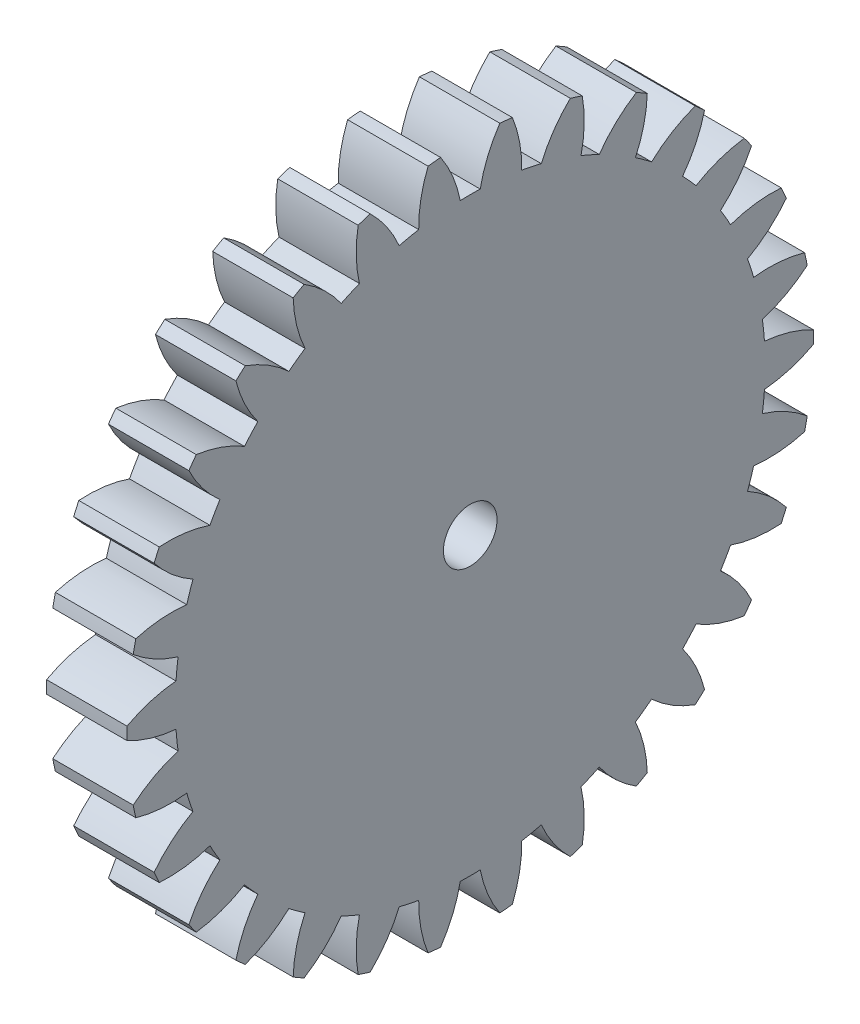
SolidWorks part; units mm, degrees
ref_plane "Plane1" through (0, 0, 0) normal (0, 0, 1) x (1, 0, 0)
ref_plane "Plane2" through (0, 0, 0) normal (0, 1, 0) x (1, 0, 0)
ref_plane "Plane3" through (0, 0, 0) normal (1, 0, 0) x (0, 0, -1)
sketch "HoldingSke" plane through (0, 0, 0) normal (0, 1, 0) x (1, 0, 0)
  line L0 (0, 0) -> (1.0825, -0.625)
  line L1 (-15, 0) -> (100, 0) construction
  line L2 (0, 0) -> (-2.1039, 2.3779)
  line L3 (0, 0) -> (-11.863, 4.5341)
  line L4 (0, 0) -> (7.479, 4.318)
  line L5 (0, 0) -> (-46.8476, -17.4728)
  line L6 (0, 0) -> (-2.4869, -1.6779)
  line L7 (-2.1039, 2.3779) -> (8.6586, 51.2059)
  line L8 (-76.2, 54.61) -> (-75.9, 54.61)
  line L9 (-71.009, 38.7566) -> (-53.1078, 45.2721)
  line L10 (-76.2, 71.12) -> (104.1128, 71.12)
  line L11 (0, 0) -> (-3, 0)
  line L12 (-76.2, 101.6) -> (-76.17, 101.6)
  line L13 (24.9733, 27.94) -> (52.9518, 28.4284)
  line L14 (24.9733, 27.94) -> (24.9743, 27.94)
  line L15 (24.9733, 27.94) -> (100.4006, 29.5858)
  line L16 (-63.627, -0.8) -> (-12.827, -0.8)
  circle A0 centre (0, 0) radius 1
  circle A1 centre (0, 0) radius 10.999
  circle A2 centre (0, 0) radius 37.5
  circle A3 centre (0, 0) radius 1
  dimension "MHD" = 21.998
  dimension "Hub_dia" = 75
  dimension "Bore" = 2
  dimension "MBD" = 2
  dimension "Num_teeth" = 30
  dimension "Pitch" = 1.25
  dimension "Overall_len" = 50
  dimension "Show_teeth" = 30
  dimension "Thickness" = 3
  dimension "OAL" = 50.0001
  dimension "T_dim" = 0.3
  dimension "Ap" = 20
  dimension "H" = 19.05
  dimension "Pitch_radius" = 180.3128
  dimension "Width" = 3
  dimension "Backlash" = 0.03
  dimension "Addendum_fac" = 1
  dimension "Dedendum_fac" = 1.25
  dimension "Clearance_fac" = 0.25
  dimension "Dedendum_add" = 0.001
  dimension "Module" = 0.8
sketch "BasProSke" plane through (0, 0, 0) normal (0, 1, 0) x (1, 0, 0)
  line L0 (-10, 0) -> (60, 0) construction
  line L1 (0, 0) -> (0, 12.8)
  line L2 (0, 0) -> (3, 0)
  line L3 (3, 0) -> (3, 12.8)
  line L4 (3, 12.8) -> (0, 12.8)
  dimension "Thickness" = 3
  dimension "Diameter" = 25.6
revolve "Base-Revolve" add sketch "BasProSke" angle 360 about L0
sketch "TooCutSke" plane through (0, 0, 0) normal (1, 0, 0) x (0, 0, -1)
  line L1 (0, 0) -> (0, 107) construction
  line L2 (0, 0) -> (-0.6805, 11.9807) construction
  line L3 (0, 0) -> (-2.5058, 23.8411) construction
  line L4 (-0.6805, 11.9807) -> (-1.2529, 11.9205) construction
  arc A0 (0.3724, 10.9927) -> (-0.3724, 10.9927) centre (0, 0) ccw
  arc A1 (1.1205, 12.7764) -> (-1.1205, 12.7764) centre (0, 0) ccw
  circle A2 centre (0, 0) radius 12 construction
  circle A3 centre (0, 0) radius 11.2763 construction
  arc A4 (-0.3724, 10.9927) -> (-1.1205, 12.7764) centre (-5.0822, 10.0661) ccw
  arc A5 (1.1205, 12.7764) -> (0.3724, 10.9927) centre (5.0822, 10.0661) ccw
  dimension "Root_dia" = 21.998
  dimension "Overcut_dia" = 25.6508
  dimension "Pitch_dia" = 24
  dimension "Base_dia" = 22.5526
  dimension "Flank_rad" = 4.8
  dimension "Half_ang" = 6
  dimension "Half_CT" = 0.5755
extrude "ToothCut" cut sketch "TooCutSke" along normal through all
fillet "Breaks" [suppressed] radius 0.016
fillet "RootFillets" [suppressed] radius 0.201
pattern_circular "TeethCuts" count 30 every 12 about axis through (-10, 0, 0) along (1, 0, 0) of "ToothCut", "RootFillets", "Breaks"
sketch "HubNeaOneSke" plane through (0, 0, 0) normal (-1, 0, 0) x (0, 0, 1)
  circle A0 centre (0, 0) radius 10.999
  dimension "Diameter" = 21.998
extrude "HubNearOne" [suppressed] add sketch "HubNeaOneSke" along normal blind 47.0001
sketch "HubNeaBotSke" plane through (0, 0, 0) normal (-1, 0, 0) x (0, 0, 1)
  circle A0 centre (0, 0) radius 10.999
  dimension "Diameter" = 21.998
extrude "HubNearBoth" [suppressed] add sketch "HubNeaBotSke" along normal blind 23.5
ref_plane "FarPln" through (3, 0, 0) normal (1, 0, 0) x (0, 0, -1)
sketch "HubFarSke" plane through (3, 0, 0) normal (1, 0, 0) x (0, 0, -1)
  circle A0 centre (0, 0) radius 10.999
  dimension "Diameter" = 21.998
extrude "HubFar" [suppressed] add sketch "HubFarSke" along normal blind 23.5
sketch "BorSke" plane through (0, 0, 0) normal (1, 0, 0) x (0, 0, -1)
  circle A0 centre (0, 0) radius 1
  dimension "Diameter" = 2
extrude "Bore" cut sketch "BorSke" along normal mid plane 100.0001
sketch "KeySke" plane through (0, 0, 0) normal (1, 0, 0) x (0, 0, -1)
  line L0 (-0.4, 0) -> (-0.4, 1.3)
  line L1 (-0.4, 1.3) -> (0.4, 1.3)
  line L2 (0.4, 1.3) -> (0.4, 0)
  line L3 (0, 0) -> (0, 34) construction
  line L4 (-0.4, 0) -> (0.4, 0)
  dimension "Offset" = 1.3
  dimension "Width" = 0.8
extrude "Keyway" [suppressed] cut sketch "KeySke" along normal mid plane 100.0001
pattern_circular "Keyway2" [suppressed] count 2 every 90 about axis through (-10, 0, 0) along (1, 0, 0)
equation "' \"Module@HoldingSke\" = 6.35"
equation "' \"Num_teeth@HoldingSke\" = 12"
equation "' \"Ap@HoldingSke\" =  20"
equation "' \"Ap@HoldingSke\" = 20"
equation "' \"Width@HoldingSke\" = 0.5 * 25.4"
equation "' \"Hub_dia@HoldingSke\"= 1 * 25.4"
equation "' \"Hub_dia@HoldingSke\" = 1 * 25.4"
equation "' \"Overall_len@HoldingSke\" = 1.0 * 25.4"
equation "' \"Bore@HoldingSke\" = 0.75 * 25.4"
equation "' \"T_dim@HoldingSke\" = 0.1 * 25.4"
equation "' \"Width@KeySke\" = 0.25 * 25.4"
equation "' \"Show_teeth@HoldingSke\" = 13"
equation "' \"Backlash@HoldingSke\" = 0.009 * 25.4"
equation "' \"Addendum_fac@HoldingSke\" = 1.0"
equation "' \"Dedendum_fac@HoldingSke\" = 1.25"
equation "' \"Dedendum_add@HoldingSke\" = 0.00005 * 25.4"
equation "' \"Clearance_fac@HoldingSke\" = 0.25"
equation "\"Pitch@HoldingSke\" = 1 / \"Module@HoldingSke\""
equation "\"Overcut_dia@TooCutSke\" = (\"Num_teeth@HoldingSke\" + 2 * \"Addendum_fac@HoldingSke\") / \"Pitch@HoldingSke\" + 0.002 * 25.4"
equation "\"Pitch_dia@TooCutSke\" = \"Num_teeth@HoldingSke\" / \"Pitch@HoldingSke\""
equation "\"Base_dia@TooCutSke\" = \"Num_teeth@HoldingSke\" / \"Pitch@HoldingSke\" * cos((\"Ap@HoldingSke\"  * 3.14159265 / 180))"
equation "\"Root_dia@TooCutSke\" = (\"Num_teeth@HoldingSke\" + 2) / \"Pitch@HoldingSke\" - 2 * (\"Addendum_fac@HoldingSke\" + \"Dedendum_fac@HoldingSke\") / \"Pitch@HoldingSke\" - \"Dedendum_add@HoldingSke\" * 2"
equation "\"Half_ang@TooCutSke\" = 180 / \"Num_teeth@HoldingSke\""
equation "\"Half_CT@TooCutSke\" = \"Num_teeth@HoldingSke\" / \"Pitch@HoldingSke\" * sin((3.14159265 / 2 / \"Num_teeth@HoldingSke\")) / 2 - 7 * \"Backlash@HoldingSke\" / 4"
equation "\"Flank_rad@TooCutSke\" = \"Num_teeth@HoldingSke\" / \"Pitch@HoldingSke\" / 5"
equation "\"Radius@RootFillets\" = \"Clearance_fac@HoldingSke\" / \"Pitch@HoldingSke\" + \"Dedendum_add@HoldingSke\""
equation "\"Break_rad@Breaks\" = 0.02 / \"Pitch@HoldingSke\""
equation "\"Thickness@HoldingSke\" = \"Width@HoldingSke\""
equation "\"OAL@HoldingSke\" = \"Thickness@HoldingSke\""
equation "\"MHD@HoldingSke\" = (\"Num_teeth@HoldingSke\" + 2) / \"Pitch@HoldingSke\" - 2 * (\"Addendum_fac@HoldingSke\" + \"Dedendum_fac@HoldingSke\")  / \"Pitch@HoldingSke\" - \"Dedendum_add@HoldingSke\" * 2"
equation "\"MBD@HoldingSke\" = (\"Num_teeth@HoldingSke\" + 2) / \"Pitch@HoldingSke\" - 2 * (\"Addendum_fac@HoldingSke\" + \"Dedendum_fac@HoldingSke\")  / \"Pitch@HoldingSke\" - \"Dedendum_add@HoldingSke\" * 2 - 0.002 * 25.4"
equation "\"MHD@HoldingSke\" = ((sgn( \"MHD@HoldingSke\" - \"Hub_dia@HoldingSke\" )-1)*( \"MHD@HoldingSke\" - \"Hub_dia@HoldingSke\" ))/-2+ \"Hub_dia@HoldingSke\""
equation "\"MBD@HoldingSke\" = ((sgn( \"MBD@HoldingSke\" - \"Bore@HoldingSke\" )-1)*( \"MBD@HoldingSke\" - \"Bore@HoldingSke\" ))/-2+ \"Bore@HoldingSke\""
equation "\"OAL@HoldingSke\" = ((sgn( \"OAL@HoldingSke\" - \"Overall_len@HoldingSke\" )+1)*( \"OAL@HoldingSke\" - \"Overall_len@HoldingSke\" ))/2 + \"Overall_len@HoldingSke\" + 0.000002 * 25.4"
equation "\"Num_teeth@TeethCuts\" = int( \"Show_teeth@HoldingSke\" ) + 1"
equation "\"Num_teeth@TeethCuts\" = ((sgn( \"Num_teeth@TeethCuts\" - \"Num_teeth@HoldingSke\" )-1)*( \"Num_teeth@TeethCuts\" - \"Num_teeth@HoldingSke\" ))/-2+ \"Num_teeth@HoldingSke\""
equation "\"Num_teeth@TeethCuts\" = ((sgn( \"Num_teeth@TeethCuts\" - 2.0)+1)*( \"Num_teeth@TeethCuts\" - 2.0))/2 +2.0"
equation "\"Angle@TeethCuts\" = 360.0 / \"Num_teeth@HoldingSke\""
equation "\"Diameter@BasProSke\" = (\"Num_teeth@HoldingSke\" + 2 * \"Addendum_fac@HoldingSke\") / \"Pitch@HoldingSke\""
equation "\"Thickness@BasProSke\"  = \"Thickness@HoldingSke\""
equation "' \"Fillet_rad@BasProSke\" =  \"Thickness@HoldingSke\" * 0.05"
equation "' \"Fillet_rad@BasProSke\" = \"Thickness@HoldingSke\" * 0.05"
equation "\"MHD@HoldingSke\" = ((sgn( \"MHD@HoldingSke\" - \"Root_dia@TooCutSke\" )-1)*( \"MHD@HoldingSke\" - \"Root_dia@TooCutSke\" ))/-2+ \"Root_dia@TooCutSke\""
equation "\"Diameter@HubNeaOneSke\" = \"MHD@HoldingSke\""
equation "\"Length@HubNearOne\" = \"OAL@HoldingSke\" - \"Thickness@BasProSke\""
equation "\"Diameter@HubNeaBotSke\" = \"MHD@HoldingSke\""
equation "\"Length@HubNearBoth\" = ( \"OAL@HoldingSke\" - \"Thickness@BasProSke\" ) / 2.0"
equation "\"Thickness@FarPln\" = \"Thickness@BasProSke\""
equation "\"Diameter@HubFarSke\" = \"MHD@HoldingSke\""
equation "\"Length@HubFar\" = ( \"OAL@HoldingSke\" - \"Thickness@BasProSke\" ) / 2.0"
equation "\"Diameter@BorSke\" = \"MBD@HoldingSke\""
equation "\"D1@Bore\" = \"OAL@HoldingSke\" * 2.0"
equation "\"D1@Keyway\" = \"OAL@HoldingSke\" * 2.0"
equation "\"Offset@KeySke\" = \"T_dim@HoldingSke\" + \"MBD@HoldingSke\" / 2.0"
